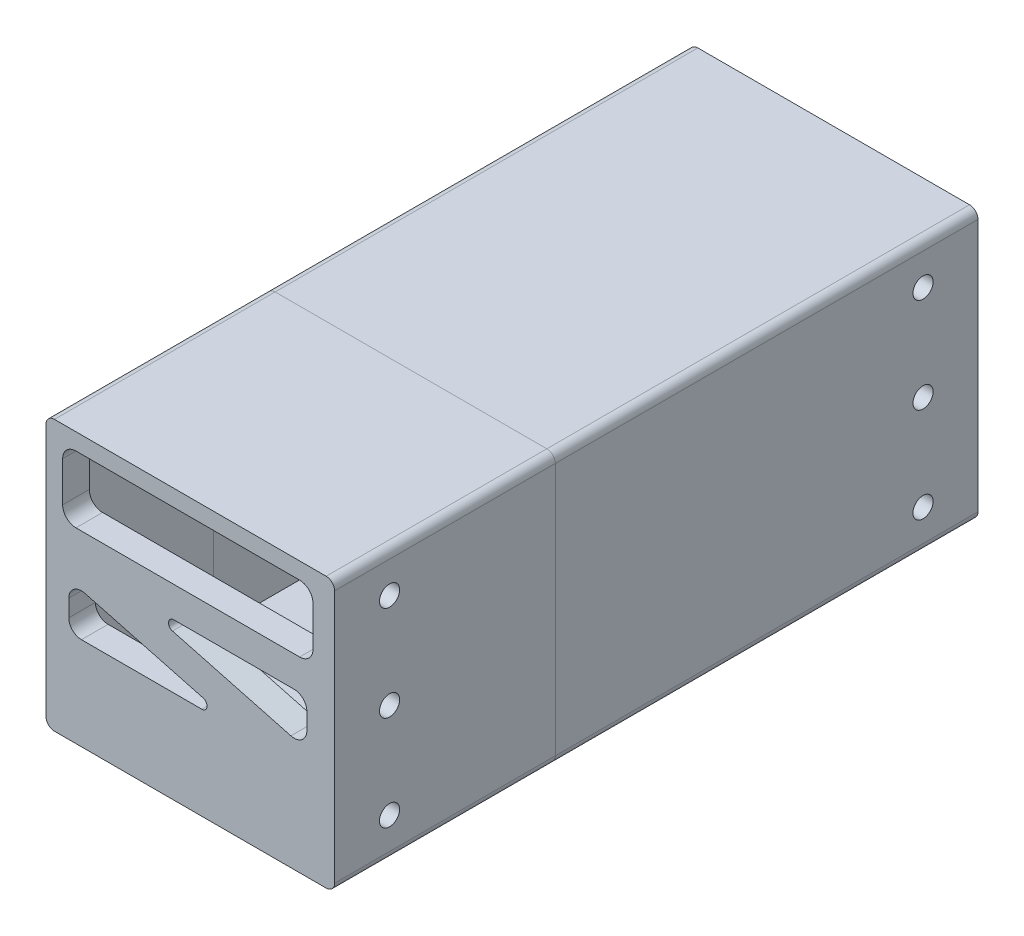
SolidWorks part; units mm, degrees
material "ABS"
ref_plane "X-Y Datum" through (0, 0, 0) normal (0, 0, 1) x (1, 0, 0)
ref_plane "X-Z Datum" through (0, 0, 0) normal (0, 1, 0) x (1, 0, 0)
ref_plane "Y-Z Datum" through (0, 0, 0) normal (1, 0, 0) x (0, 0, -1)
sketch "Sketch1" plane through (0, 0, 0) normal (0, 0, 1) x (1, 0, 0)
  line L0 (-42.608, 40.576) -> (42.608, 40.576)
  line L1 (-38.608, 36.576) -> (38.608, 36.576) construction
  line L2 (-38.608, 36.576) -> (-38.608, -36.576) construction
  line L3 (-38.608, -36.576) -> (38.608, -36.576) construction
  line L4 (38.608, 36.576) -> (38.608, -36.576) construction
  line L5 (-38.608, 36.576) -> (38.608, -36.576) construction
  line L6 (-38.608, -36.576) -> (38.608, 36.576) construction
  line L11 (42.608, 40.576) -> (42.608, -40.576)
  line L12 (-42.608, -40.576) -> (42.608, -40.576)
  line L13 (-42.608, 40.576) -> (-42.608, -40.576)
  point P0 (0, 0)
  point P6 (0, 0)
  dimension "D1" = 77.216
  dimension "D2" = 4
  dimension "D3" = 73.152
extrude "Boss-Extrude1" add sketch "Sketch1" along normal blind 185.308
ref_plane "Plane1" through (0, 0, 127) normal (0, 0, -1) x (-1, 0, 0)
split "Split1" trim tools "Plane1" bodies to split 101 resulting bodies 102 103
shell "Shell2" thickness 4
shell "Shell3" thickness 4
fillet "Fillet1" [suppressed] radius 2.54
fillet "Fillet2" [suppressed] radius 2.54
sketch "Sketch4" plane through (0, 0, 127) normal (0, 0, 1) x (1, 0, 0)
  line L14 (40.608, -38.576) -> (40.608, 38.576)
  line L15 (-40.608, -38.576) -> (40.608, -38.576)
  line L16 (-40.608, 38.576) -> (-40.608, -38.576)
  line L17 (40.608, 38.576) -> (-40.608, 38.576)
  line L18 (40.608, -38.576) -> (40.608, 38.576)
  line L19 (-40.608, -38.576) -> (40.608, -38.576)
  line L20 (-40.608, 38.576) -> (-40.608, -38.576)
  line L21 (40.608, 38.576) -> (-40.608, 38.576)
  line L22 (-38.608, 36.576) -> (-38.608, -36.576)
  line L23 (-38.608, -36.576) -> (38.608, -36.576)
  line L24 (38.608, -36.576) -> (38.608, 36.576)
  line L25 (38.608, 36.576) -> (-38.608, 36.576)
  line L26 (-38.608, 36.576) -> (-38.608, -36.576)
  line L27 (-38.608, -36.576) -> (38.608, -36.576)
  line L28 (38.608, -36.576) -> (38.608, 36.576)
  line L29 (38.608, 36.576) -> (-38.608, 36.576)
  dimension "D1" = 2
  dimension "D2" = 0
extrude "Boss-Extrude2" add sketch "Sketch4" along normal blind 20
sketch "Sketch5" plane through (0, 0, 127) normal (0, 0, -1) x (-1, 0, 0)
  line L0 (40.989, 38.957) -> (-40.989, 38.957)
  line L1 (-40.989, 38.957) -> (-40.989, -38.957)
  line L2 (-40.989, -38.957) -> (40.989, -38.957)
  line L3 (40.989, -38.957) -> (40.989, 38.957)
  line L4 (38.608, -36.576) -> (38.608, 36.576)
  line L5 (-38.608, -36.576) -> (38.608, -36.576)
  line L6 (-38.608, 36.576) -> (-38.608, -36.576)
  line L7 (38.608, 36.576) -> (-38.608, 36.576)
  line L8 (38.608, -36.576) -> (38.608, 36.576)
  line L9 (-38.608, -36.576) -> (38.608, -36.576)
  line L10 (-38.608, 36.576) -> (-38.608, -36.576)
  line L11 (38.608, 36.576) -> (-38.608, 36.576)
  line L12 (-40.608, 38.576) -> (-40.608, -38.576)
  line L13 (-40.608, -38.576) -> (40.608, -38.576)
  line L14 (40.608, -38.576) -> (40.608, 38.576)
  line L15 (40.608, 38.576) -> (-40.608, 38.576)
  line L16 (-40.608, 38.576) -> (-40.608, -38.576) construction
  line L17 (-40.608, -38.576) -> (40.608, -38.576) construction
  line L18 (40.608, -38.576) -> (40.608, 38.576) construction
  line L19 (40.608, 38.576) -> (-40.608, 38.576) construction
  line L24 (-42.608, -40.576) -> (42.608, -40.576)
  line L25 (42.608, -40.576) -> (42.608, 40.576)
  line L26 (42.608, 40.576) -> (-42.608, 40.576)
  line L27 (-42.608, 40.576) -> (-42.608, -40.576)
  line L28 (-42.608, -40.576) -> (42.608, -40.576)
  line L29 (42.608, -40.576) -> (42.608, 40.576)
  line L30 (42.608, 40.576) -> (-42.608, 40.576)
  line L31 (-42.608, 40.576) -> (-42.608, -40.576)
  line M21 (38.608, -36.576) -> (-38.608, -36.576)
  line M22 (-38.608, -36.576) -> (-38.608, 36.576)
  line M23 (-38.608, 36.576) -> (38.608, 36.576)
  line M24 (38.608, 36.576) -> (38.608, -36.576)
  dimension "D1" = 0
  dimension "D2" = 0
  dimension "D3" = 0.381
  dimension "D4" = 0
extrude "Cut-Extrude2" cut sketch "Sketch5" against normal blind 20 contours L2 L3 L0 L1 M24 M21 M22 M23
sketch "Sketch6" plane through (0, 0, 185.308) normal (0, 0, 1) x (1, 0, 0)
  line L0 (0, -40.576) -> (0, 40.576) construction
  line L1 (-42.608, -40.576) -> (42.608, -40.576) construction
  line L2 (42.608, 40.576) -> (-42.608, 40.576) construction
  line L4 (-37.608, 35.576) -> (37.608, 35.576)
  line L5 (-37.608, 35.576) -> (-37.608, 15.576)
  line L6 (-37.608, 15.576) -> (37.608, 15.576)
  line L7 (37.608, 35.576) -> (37.608, 15.576)
  line L8 (-37.608, 35.576) -> (37.608, 15.576) construction
  line L9 (-37.608, 15.576) -> (37.608, 35.576) construction
  line L10 (38.608, 36.576) -> (-38.608, 36.576) construction
  line L11 (38.608, -36.576) -> (38.608, 36.576) construction
  point P6 (0, 25.576)
  dimension "D1" = 20
  dimension "D2" = 1
  dimension "D3" = 1
extrude "Cut-Extrude3" cut sketch "Sketch6" against normal blind 4
fillet "Fillet3" radius 4 4 edges at (37.608, 35.576, 183.308) (37.608, 15.576, 183.308) (-37.608, 35.576, 183.308) (-37.608, 15.576, 183.308)
sketch "Sketch7" plane through (0, 0, 185.308) normal (0, 0, 1) x (1, 0, 0)
  line L0 (-37.608, 31.576) -> (-37.608, 19.576) construction
  line L1 (-33.608, 15.576) -> (33.608, 15.576) construction
  line L2 (33.608, 35.576) -> (-33.608, 35.576) construction
  line L3 (37.608, 19.576) -> (37.608, 31.576) construction
  line L4 (-42.608, 40.576) -> (-42.608, -40.576)
  line L5 (-42.608, -40.576) -> (42.608, -40.576)
  line L6 (42.608, -40.576) -> (42.608, 40.576)
  line L7 (42.608, 40.576) -> (-42.608, 40.576)
  line L8 (-42.608, 40.576) -> (-42.608, -40.576)
  line L9 (-42.608, -40.576) -> (42.608, -40.576)
  line L10 (42.608, -40.576) -> (42.608, 40.576)
  line L11 (42.608, 40.576) -> (-42.608, 40.576)
  line L12 (-33.608, 15.576) -> (33.608, 15.576)
  line L13 (-37.608, 31.576) -> (-37.608, 19.576)
  line L14 (33.608, 35.576) -> (-33.608, 35.576)
  line L15 (37.608, 19.576) -> (37.608, 31.576)
  arc A0 (-37.608, 19.576) -> (-33.608, 15.576) centre (-33.608, 19.576) ccw construction
  arc A1 (-33.608, 35.576) -> (-37.608, 31.576) centre (-33.608, 31.576) ccw construction
  arc A2 (37.608, 31.576) -> (33.608, 35.576) centre (33.608, 31.576) ccw construction
  arc A3 (33.608, 15.576) -> (37.608, 19.576) centre (33.608, 19.576) ccw construction
  arc A12 (-37.608, 19.576) -> (-33.608, 15.576) centre (-33.608, 19.576) ccw
  arc A13 (-33.608, 35.576) -> (-37.608, 31.576) centre (-33.608, 31.576) ccw
  arc A14 (37.608, 31.576) -> (33.608, 35.576) centre (33.608, 31.576) ccw
  arc A15 (33.608, 15.576) -> (37.608, 19.576) centre (33.608, 19.576) ccw
  dimension "D1" = 0
extrude "Boss-Extrude3" add sketch "Sketch7" along normal blind 4
sketch "Sketch8" plane through (0, 0, 0) normal (0, 0, -1) x (-1, 0, 0)
  line L4 (42.608, 40.576) -> (-42.608, 40.576)
  line L5 (-42.608, 40.576) -> (-42.608, -40.576)
  line L6 (-42.608, -40.576) -> (42.608, -40.576)
  line L7 (42.608, -40.576) -> (42.608, 40.576)
  line L8 (42.608, 40.576) -> (-42.608, 40.576)
  line L9 (-42.608, 40.576) -> (-42.608, -40.576)
  line L10 (-42.608, -40.576) -> (42.608, -40.576)
  line L11 (42.608, -40.576) -> (42.608, 40.576)
  dimension "D1" = 0
extrude "Boss-Extrude4" add sketch "Sketch8" along normal blind 4
ref_plane "Plane2" through (0, 0, 92.654) normal (0, 0, 1) x (1, 0, 0)
sketch "Sketch9" plane through (0, 0, 189.308) normal (0, 0, 1) x (1, 0, 0)
  line L0 (-42.608, 0) -> (42.608, 0) construction
  line L1 (-42.608, 40.576) -> (-42.608, -40.576) construction
  line L2 (42.608, -40.576) -> (42.608, 40.576) construction
  line L3 (-42.608, -27.876) -> (42.608, -27.876) construction
  line L4 (-42.608, -40.576) -> (42.608, -40.576) construction
  line L5 (-42.608, -27.876) -> (0, -27.876) construction
  line L6 (0, -27.876) -> (-21.304, -27.876) construction
  line L7 (-21.304, -27.876) -> (-21.304, -24.0766) construction
  line L8 (0, -27.876) -> (42.608, -27.876) construction
  line L9 (21.304, -27.876) -> (21.304, -24.0766) construction
  circle A0 centre (-21.304, -27.876) radius 3.025
  circle A1 centre (0, -27.876) radius 3.025
  circle A2 centre (21.304, -27.876) radius 3.025
  dimension "D2" = 6.05
  dimension "D1" = 12.7
extrude "Cut-Extrude4" cut sketch "Sketch9" against normal blind 6 contours A0 | A1 | A2
mirror "Mirror1" about plane through (0, 0, 92.654) normal (0, 0, 1) of "Cut-Extrude4"
sketch "Sketch10" plane through (0, 0, 4) normal (0, 0, 1) x (1, 0, 0)
  line L4 (-38.608, 36.576) -> (-38.608, -36.576)
  line L5 (-38.608, -36.576) -> (38.608, -36.576)
  line L6 (38.608, -36.576) -> (38.608, 36.576)
  line L7 (38.608, 36.576) -> (-38.608, 36.576)
  line L8 (-38.608, 36.576) -> (-38.608, -36.576)
  line L9 (-38.608, -36.576) -> (38.608, -36.576)
  line L10 (38.608, -36.576) -> (38.608, 36.576)
  line L11 (38.608, 36.576) -> (-38.608, 36.576)
  dimension "D1" = 0
other "Save Bodies1"
extrude "Boss-Extrude5" add sketch "Sketch10" along normal blind 4.5
sketch "Sketch11" plane through (0, 0, -4) normal (0, 0, -1) x (-1, 0, 0)
  line L4 (42.608, 40.576) -> (-42.608, 40.576)
  line L5 (-42.608, 40.576) -> (-42.608, -40.576)
  line L6 (-42.608, -40.576) -> (42.608, -40.576)
  line L7 (42.608, -40.576) -> (42.608, 40.576)
  line L9 (-42.608, 40.576) -> (-42.608, -40.576)
  line L10 (-42.608, -40.576) -> (42.608, -40.576)
  line L11 (42.608, -40.576) -> (42.608, 40.576)
  line L12 (42.608, 40.576) -> (-42.608, 40.576) construction
  line L13 (42.608, 40.576) -> (-42.608, 40.576)
  line L14 (26.098, 27.876) -> (11.7275, 27.876)
  line L15 (-29.908, -1.263) -> (-29.908, -11.766)
  line L16 (29.908, 13.6269) -> (29.908, 24.066)
  line L17 (29.908, -7.7274) -> (29.908, 27.876)
  line L18 (-26.098, -15.576) -> (-11.6396, -15.576)
  line L19 (29.908, 27.876) -> (29.908, -7.7274)
  line L20 (23.8588, 10.5443) -> (9.4882, 20.9835)
  line L21 (-29.908, 27.876) -> (29.908, -15.576)
  line L22 (-29.908, -15.4483) -> (-29.908, 20.0274)
  line L23 (-23.8588, 1.8195) -> (-9.4003, -8.6835)
  line L24 (-29.908, 40.576) -> (-29.908, -40.576) construction
  line L25 (-42.608, -15.576) -> (42.608, -15.576) construction
  line L26 (29.908, -40.576) -> (29.908, 40.576) construction
  line L27 (42.608, 27.876) -> (-42.608, 27.876) construction
  line L28 (-33.6401, 22.7385) -> (26.1759, -20.7135)
  line L29 (-26.1759, 33.0135) -> (33.6401, -10.4385)
  circle A0 centre (21.304, -27.876) radius 3.025 construction
  circle A1 centre (0, -27.876) radius 3.025 construction
  circle A2 centre (-21.304, -27.876) radius 3.025 construction
  circle A3 centre (21.304, -27.876) radius 3.025
  circle A12 centre (0, -27.876) radius 3.025
  circle A13 centre (-21.304, -27.876) radius 3.025
  arc A14 (-29.908, -1.263) -> (-23.8588, 1.8195) centre (-26.098, -1.263) cw
  arc A15 (-26.098, -15.576) -> (-29.908, -11.766) centre (-26.098, -11.766) cw
  arc A16 (-9.4003, -8.6835) -> (-11.6396, -15.576) centre (-11.6396, -11.766) cw
  arc A17 (29.908, 13.6269) -> (23.8588, 10.5443) centre (26.098, 13.6269) cw
  arc A18 (9.4882, 20.9835) -> (11.7275, 27.876) centre (11.7275, 24.066) cw
  arc A19 (26.098, 27.876) -> (29.908, 24.066) centre (26.098, 24.066) cw
  arc A23 (-29.908, 20.0274) -> (-22.4439, 30.3025) centre (-26.1759, 25.1649) cw
  arc A25 (29.908, -7.7274) -> (22.4439, -18.0025) centre (26.1759, -12.8649) cw
  point P38 (-29.908, 20.0274)
  point P60 (29.908, -7.7274)
  dimension "D4" = 17.5777
  dimension "D5" = 17.526
  dimension "D6" = 3.81
  dimension "D1" = 0
  dimension "D2" = 12.7
  dimension "D3" = 25
  dimension "D7" = 6.35
  dimension "D8" = 6.35
extrude "Cut-Extrude5" cut sketch "Sketch11" against normal up to surface (12.5 mm away)
sketch "Sketch12" plane through (0, 0, 189.308) normal (0, 0, 1) x (1, 0, 0)
  line L0 (-30.9726, -0.1002) -> (4.6151, -9.5785)
  line L1 (-4.2066, 6.35) -> (31.9531, 6.35)
  line L2 (-35.7631, -3.7819) -> (-35.7631, -8.89)
  line L3 (-31.9531, -12.7) -> (4.2066, -12.7)
  line L4 (35.7631, 2.54) -> (35.7631, -2.5681)
  line L5 (-35.7631, 6.35) -> (35.7631, -12.7) construction
  line L6 (-35.7631, -12.7) -> (35.7631, 6.35) construction
  line L7 (-4.6151, 3.2285) -> (30.9726, -6.2498)
  line L8 (-34.4763, 11.1816) -> (37.0499, -7.8684) construction
  line L9 (-37.0499, 1.5184) -> (34.4763, -17.5316) construction
  arc A0 (35.7631, -2.5681) -> (30.9726, -6.2498) centre (31.9531, -2.5681) cw
  arc A1 (35.7631, 2.54) -> (31.9531, 6.35) centre (31.9531, 2.54) ccw
  arc A2 (-35.7631, -3.7819) -> (-30.9726, -0.1002) centre (-31.9531, -3.7819) cw
  arc A3 (-31.9531, -12.7) -> (-35.7631, -8.89) centre (-31.9531, -8.89) cw
  arc A4 (4.2066, -12.7) -> (4.6151, -9.5785) centre (4.2066, -11.1125) ccw
  arc A5 (-4.2066, 6.35) -> (-4.6151, 3.2285) centre (-4.2066, 4.7625) ccw
  point P0 (0, -3.175)
  dimension "D2" = 3.81
  dimension "D5" = 1.5875
  dimension "D1" = 3.175
  dimension "D3" = 5
  dimension "D4" = 5
extrude "Cut-Extrude6" cut sketch "Sketch12" against normal up to surface (8 mm away) up to face at (0, 25.576, 181.308)
other "Save Bodies2"
sketch "Sketch13" plane through (42.608, 0, 0) normal (-1, 0, 0) x (0, 0, 1)
  line L1 (127, 40.576) -> (189.308, 40.576)
  line L2 (127, 40.576) -> (127, -40.576)
  line L3 (127, -40.576) -> (189.308, -40.576)
  line L4 (189.308, 40.576) -> (189.308, -40.576)
extrude "Boss-Extrude7" add sketch "Sketch13" against normal blind 1.5
sketch "Sketch15" plane through (42.608, 0, 0) normal (1, 0, 0) x (0, 0, -1)
  line L1 (-127, 40.576) -> (4, 40.576)
  line L2 (-127, 40.576) -> (-127, -40.576)
  line L3 (-127, -40.576) -> (4, -40.576)
  line L4 (4, 40.576) -> (4, -40.576)
extrude "Boss-Extrude8" add sketch "Sketch15" along normal blind 1.5
ref_plane "Plane3" through (0, 0, 123) normal (0, 0, -1) x (-1, 0, 0)
split "Split2" trim tools "Plane3" bodies to split 131 resulting bodies 132 133
sketch "Sketch16" plane through (44.108, 0, 0) normal (1, 0, 0) x (0, 0, -1)
  line L0 (-179.656, 0) -> (49820.344, 0) construction
  line L1 (-189.308, -40.576) -> (-189.308, 40.576) construction
  line L2 (-179.656, 28.575) -> (49820.344, 28.575) construction
  line L3 (-175.6709, -28.575) -> (49824.3291, -28.575) construction
  line L4 (-172.798, 33.6302) -> (-172.798, -49966.3698) construction
  line L5 (-12.51, 35.9206) -> (-12.51, -49964.0794) construction
  line L6 (4, -40.576) -> (4, 40.576) construction
  circle A0 centre (-172.798, 28.575) radius 3.025
  circle A1 centre (-172.798, 0) radius 3.025
  circle A2 centre (-172.798, -28.575) radius 3.025
  circle A3 centre (-12.51, 28.575) radius 3.025
  circle A4 centre (-12.51, 0) radius 3.025
  circle A5 centre (-12.51, -28.575) radius 3.025
  point P4 (-189.308, 0)
  dimension "D1" = 28.575
  dimension "D2" = 28.575
  dimension "D3" = 16.51
  dimension "D4" = 16.51
fillet "Fillet4" radius 2.54 4 edges at (44.108, -40.576, 156.154) (44.108, 40.576, 156.154) (-42.608, 40.576, 156.154) (-42.608, -40.576, 156.154)
fillet "Fillet5" radius 2.54 4 edges at (44.108, 40.576, 59.5) (-42.608, 40.576, 59.5) (44.108, -40.576, 59.5) (-42.608, -40.576, 59.5)
extrude "Cut-Extrude9" cut sketch "Sketch16" against normal blind 19.5
sketch "Sketch18" plane through (0, 0, 189.308) normal (0, 0, 1) x (1, 0, 0)
  line L1 (-30.9166, -18.4897) -> (31.2929, -18.4897)
  line L2 (-30.9166, -18.4897) -> (-30.9166, -35.4334)
  line L3 (-30.9166, -35.4334) -> (31.2929, -35.4334)
  line L4 (31.2929, -18.4897) -> (31.2929, -35.4334)
extrude "Boss-Extrude9" add sketch "Sketch18" against normal blind 8
sketch "Sketch19" plane through (0, 0, -4) normal (0, 0, -1) x (-1, 0, 0)
  line L1 (-31.4166, -20.8396) -> (29.3088, -20.8396)
  line L2 (-31.4166, -20.8396) -> (-31.4166, -35.6808)
  line L3 (-31.4166, -35.6808) -> (29.3088, -35.6808)
  line L4 (29.3088, -20.8396) -> (29.3088, -35.6808)
extrude "Boss-Extrude10" add sketch "Sketch19" against normal blind 12.5
sketch "Sketch20" plane through (0, 0, 123) normal (0, 0, 1) x (1, 0, 0)
  line L11 (-38.608, 36.576) -> (38.608, 36.576)
  line L12 (-38.608, 36.576) -> (-38.608, -36.576)
  line L13 (-38.608, -36.576) -> (38.608, -36.576)
  line L14 (-40.608, -38.576) -> (40.608, -38.576)
  line L15 (40.608, -38.576) -> (40.608, 38.576)
  line L16 (40.608, 38.576) -> (-40.608, 38.576)
  line L17 (-40.608, 38.576) -> (-40.608, -38.576)
  line L18 (-40.608, -38.576) -> (40.608, -38.576)
  line L19 (40.608, -38.576) -> (40.608, 38.576)
  line L20 (40.608, 38.576) -> (-40.608, 38.576)
  line L21 (-40.608, 38.576) -> (-40.608, -38.576)
  line L22 (38.608, 36.576) -> (38.608, -36.576)
  dimension "D1" = 2
extrude "Boss-Extrude11" add sketch "Sketch20" along normal blind 20
sketch "Sketch21" plane through (0, 0, 123) normal (0, 0, -1) x (-1, 0, 0)
  line L18 (-40.608, -38.576) -> (40.608, -38.576)
  line L19 (40.608, -38.576) -> (40.608, 38.576)
  line L20 (40.608, 38.576) -> (-40.608, 38.576)
  line L21 (-40.608, 38.576) -> (-40.608, -38.576)
  line L22 (-40.608, -38.576) -> (40.608, -38.576)
  line L23 (40.608, -38.576) -> (40.608, 38.576)
  line L24 (40.608, 38.576) -> (-40.608, 38.576)
  line L25 (-40.608, 38.576) -> (-40.608, -38.576)
  dimension "D1" = 2
extrude "Cut-Extrude10" cut sketch "Sketch21" against normal blind 20
